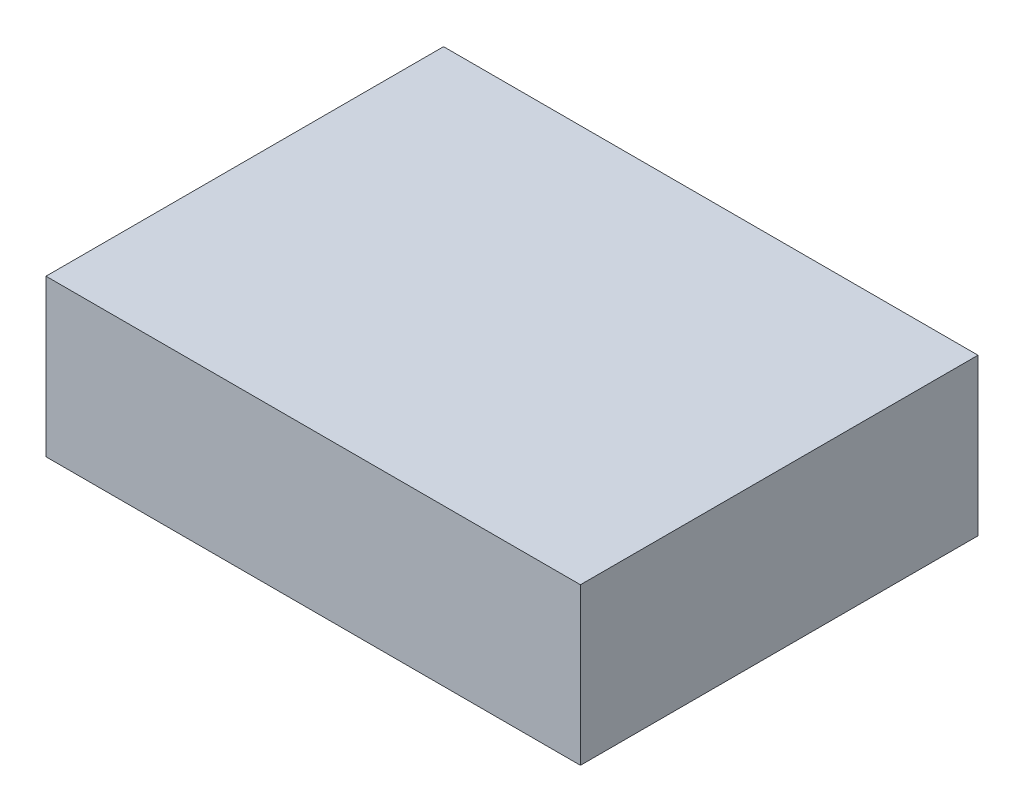
SolidWorks part; units mm, degrees
ref_plane "Front Plane" through (0, 0, 0) normal (0, 0, 1) x (1, 0, 0)
ref_plane "Top Plane" through (0, 0, 0) normal (0, 1, 0) x (1, 0, 0)
ref_plane "Right Plane" through (0, 0, 0) normal (1, 0, 0) x (0, 0, -1)
sketch "Sketch1" plane through (0, 0, 0) normal (0, 1, 0) x (1, 0, 0)
  line L1 (-130.175, 96.8375) -> (130.175, 96.8375)
  line L2 (-130.175, 96.8375) -> (-130.175, -96.8375)
  line L3 (-130.175, -96.8375) -> (130.175, -96.8375)
  line L4 (130.175, 96.8375) -> (130.175, -96.8375)
  line L5 (-130.175, 96.8375) -> (130.175, -96.8375) construction
  line L6 (-130.175, -96.8375) -> (130.175, 96.8375) construction
  point P0 (0, 0)
  dimension "D1" = 260.35
  dimension "D2" = 193.675
extrude "Boss-Extrude1" add sketch "Sketch1" along normal blind 76.2
